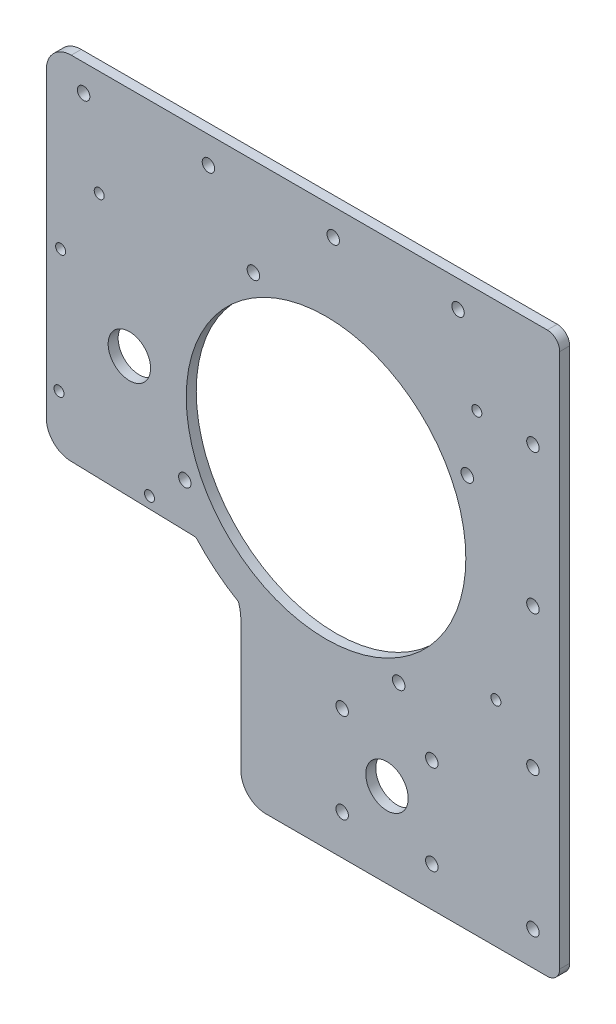
SolidWorks part; units mm, degrees
ref_plane "Front Plane" through (0, 0, 0) normal (0, 0, 1) x (1, 0, 0)
ref_plane "Top Plane" through (0, 0, 0) normal (0, 1, 0) x (1, 0, 0)
ref_plane "Right Plane" through (0, 0, 0) normal (1, 0, 0) x (0, 0, -1)
sketch "Sketch1" plane through (0, 0, 0) normal (0, 0, 1) x (1, 0, 0)
  line L0 (-49.6523, 40.6914) -> (-49.6523, -47.2098) construction
  line L5 (43.313, -35.4962) -> (-53.6504, 43.9679) construction
  line L20 (43.313, 35.4962) -> (-40.4126, -33.1192) construction
  line L35 (-112.0671, 20.8795) -> (-112.0671, -35.3689)
  line L41 (-112.0671, 20.8795) -> (-112.0671, 85.5727)
  line L46 (-34.1059, -118.665) -> (-34.1059, -66.6764)
  line L47 (-53.5655, -46.6837) -> (-102.3374, -45.3653)
  line L50 (58.6142, -128.665) -> (-24.1059, -128.665)
  line L59 (-0.0972, 95.5727) -> (-102.0671, 95.5727)
  line L60 (-0.0972, 95.5727) -> (58.6142, 95.5727)
  line L61 (58.6142, 95.5727) -> (88.6142, 95.5727)
  line L62 (93.6142, 90.5727) -> (93.6142, -123.665)
  line L63 (88.6142, -128.665) -> (58.6142, -128.665)
  line L64 (-41.9595, -34.3869) -> (-43.313, -35.4962) construction
  line L65 (-112.0671, 75.5727) -> (93.6142, 75.5727) construction
  line L66 (73.6142, -128.665) -> (73.6142, 95.5727) construction
  line L67 (92.1497, 94.1082) -> (73.6142, 75.5727) construction
  line L68 (-97.118, 84.8404) -> (82.882, 84.8404) construction
  line L69 (82.882, -115.1596) -> (82.882, 84.8404) construction
  line L70 (82.882, 84.8404) -> (-7.118, 84.8404) construction
  line L71 (82.882, 84.8404) -> (82.882, -15.1596) construction
  circle A0 centre (0, 0) radius 56
  arc A28 (18.7204, 66.7914) -> (-60.2577, -34.3591) centre (0, 0) ccw construction
  arc A31 (-102.0671, 95.5727) -> (-112.0671, 85.5727) centre (-102.0671, 85.5727) ccw
  arc A33 (-102.3374, -45.3653) -> (-112.0671, -35.3689) centre (-102.0671, -35.3689) cw
  arc A34 (-24.1059, -128.665) -> (-34.1059, -118.665) centre (-24.1059, -118.665) cw
  arc A35 (-34.1059, -66.6764) -> (-53.5655, -46.6837) centre (-54.1059, -66.6764) ccw
  circle A36 centre (0, 0) radius 54.25 construction
  circle A43 centre (-90.8661, 53.2128) radius 2
  circle A44 centre (60.4116, 53.4102) radius 2
  circle A45 centre (68.054, -43.0272) radius 2
  circle A46 centre (-70.7336, -41.6872) radius 2
  arc A47 (93.6142, -123.665) -> (88.6142, -128.665) centre (88.6142, -123.665) cw
  arc A48 (93.6142, 90.5727) -> (88.6142, 95.5727) centre (88.6142, 90.5727) ccw
  circle A52 centre (29.1136, -56.5733) radius 2.5
  circle A53 centre (-106.9876, -23.4374) radius 2
  circle A54 centre (-106.3335, 26.1978) radius 2
  circle A55 centre (82.882, 84.8404) radius 2.5 construction
  circle A59 centre (-97.118, 84.8404) radius 2.5
  circle A63 centre (82.882, -115.1596) radius 2.5
  circle A64 centre (-52.118, 84.8404) radius 2.5 [skipped]
  circle A65 centre (-7.118, 84.8404) radius 2.5 [skipped]
  circle A66 centre (37.882, 84.8404) radius 2.5 [skipped]
  circle A67 centre (82.882, 34.8404) radius 2.5 [skipped]
  circle A68 centre (82.882, -15.1596) radius 2.5 [skipped]
  circle A69 centre (82.882, -65.1596) radius 2.5 [skipped]
  circle A72 centre (-56.5733, -29.1136) radius 2.5
  circle A73 centre (-29.1136, 56.5733) radius 2.5
  circle A74 centre (56.5733, 29.1136) radius 2.5
  circle A76 centre (-78.4044, 2.7739) radius 21.64 construction
  circle A79 centre (-47.118, 84.8404) radius 2.5
  circle A80 centre (2.882, 84.8404) radius 2.5
  circle A81 centre (52.882, 84.8404) radius 2.5
  circle A82 centre (82.882, -59.1196) radius 2.5
  circle A83 centre (82.882, -3.0796) radius 2.5
  circle A84 centre (82.882, 52.9604) radius 2.5
  point P19 (3.3231, 1.8554)
  point P42 (0, 0)
  point P48 (0, 0)
  point P76 (0, 0)
  dimension "D1" = 112
  dimension "D3" = 5
  dimension "D4" = 10
  dimension "D5" = 20
  dimension "D6" = 5
  dimension "D7" = 10
  dimension "D8" = 20
  dimension "D9" = 5
  dimension "D11" = 4
  dimension "D12" = 4
  dimension "D14" = 4
  dimension "D15" = 4
  dimension "D16" = 4
  dimension "D17" = 43.28
  dimension "D2" = 20
  dimension "D10" = 5
  dimension "D13" = 4
extrude "Boss-Extrude1" add sketch "Sketch1" along normal blind 4
sketch "Sketch4" plane through (0, 0, 0) normal (0, 0, -1) x (-1, 0, 0)
  line L0 (-73.6142, -128.665) -> (-73.6142, 95.5727) construction
  line L1 (24.1059, -128.665) -> (-88.6142, -128.665) construction
  line L2 (-88.6142, 95.5727) -> (102.0671, 95.5727) construction
  line L3 (-93.6142, -123.665) -> (-93.6142, 90.5727) construction
  circle A0 centre (91.498, 2.7739) radius 45.77 construction
  circle A1 centre (0, 0) radius 45.77 construction
  circle A4 centre (0, 0) radius 64.82 construction
  circle A9 centre (0, 0) radius 57.2 construction
  circle A10 centre (78.7907, 2.7875) radius 21.64 construction
  circle A11 centre (-24.413, -94.7969) radius 27.99 construction
  circle A12 centre (0, 0) radius 69.9 construction
  circle A13 centre (-24.413, -94.7969) radius 8.5
  dimension "D1" = 91.54
  dimension "D2" = 91.54
  dimension "D3" = 55.98
  dimension "D4" = 114.4
  dimension "D5" = 129.64
  dimension "D6" = 17
  dimension "D7" = 43.28
  dimension "D8" = 139.8
  dimension "D9" = 20
extrude "Cut-Extrude2" cut sketch "Sketch4" against normal through all
sketch "Sketch6" plane through (0, 0, 4) normal (0, 0, 1) x (1, 0, 0)
  circle A0 centre (-78.7905, 2.7942) radius 21.64 construction
  circle A1 centre (0, 0) radius 57.2 construction
  circle A2 centre (-78.7905, 2.7942) radius 8.5
  dimension "D1" = 43.28
  dimension "D2" = 114.4
  dimension "D3" = 17
extrude "Cut-Extrude4" cut sketch "Sketch6" against normal through all
sketch "Sketch7" plane through (0, 0, 4) normal (0, 0, 1) x (1, 0, 0)
  line L0 (6.4525, -112.7574) -> (42.3735, -112.7574) construction
  line L1 (-24.1059, -128.665) -> (88.6142, -128.665) construction
  circle A0 centre (42.3735, -76.8364) radius 2.5
  circle A1 centre (6.4525, -112.7574) radius 2.5
  circle A2 centre (6.4525, -76.8364) radius 2.5
  circle A3 centre (42.3735, -112.7574) radius 2.5
  circle A4 centre (24.413, -94.7969) radius 25.4 construction
  dimension "D1" = 5
  dimension "D2" = 50.8
  dimension "D3" = 50.8
  dimension "D4" = 35.921
  dimension "D5" = 35.921
  dimension "D6" = 35.921
  dimension "D7" = 50.8
extrude "Cut-Extrude5" cut sketch "Sketch7" against normal through all
sketch "Sketch8" plane through (0, 0, 4) normal (0, 0, 1) x (1, 0, 0)
  line L0 (-52.1726, -46.6693) -> (-39.0286, -47.6353)
  line L4 (-39.0286, -47.6353) -> (-0.2182, -69.9997)
  arc A0 (-52.1726, -46.6693) -> (-0.2182, -69.9997) centre (0, 0) ccw
extrude "Boss-Extrude3" add sketch "Sketch8" against normal blind 4
